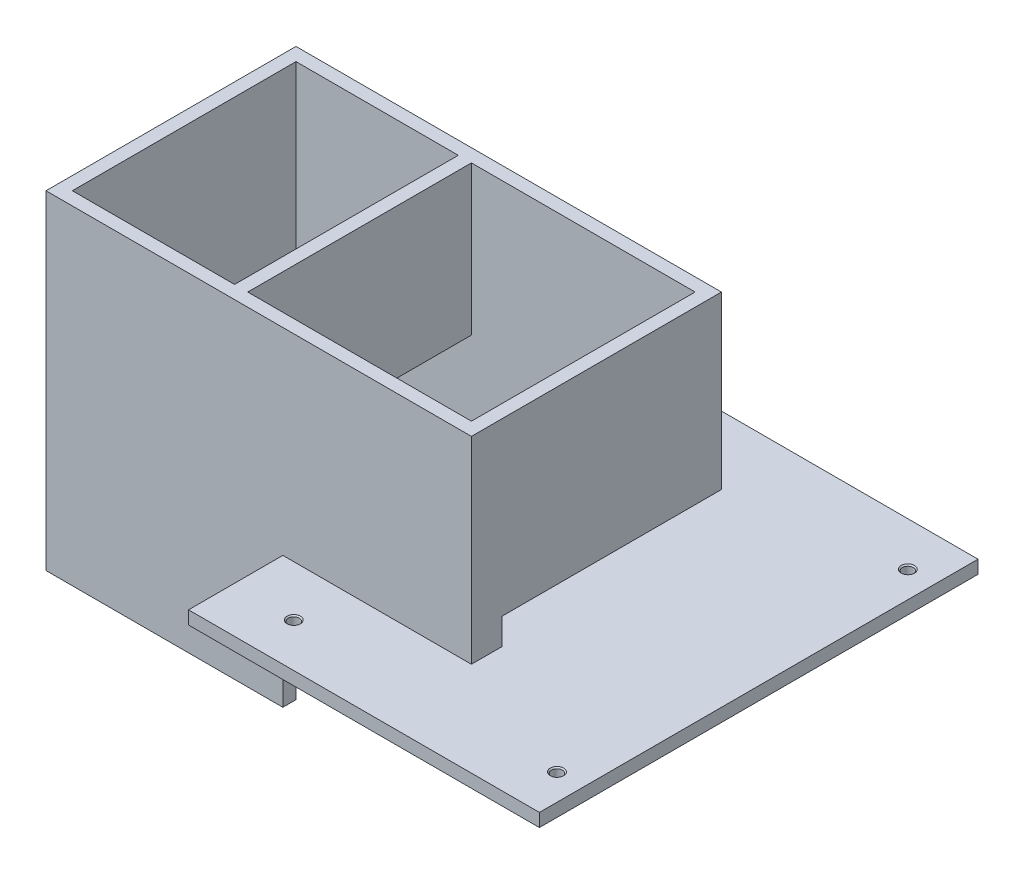
SolidWorks part; units mm, degrees
ref_plane "前视基准面" through (0, 0, 0) normal (0, 0, 1) x (1, 0, 0)
ref_plane "上视基准面" through (0, 0, 0) normal (0, 1, 0) x (1, 0, 0)
ref_plane "右视基准面" through (0, 0, 0) normal (1, 0, 0) x (0, 0, -1)
sketch "草图1" plane through (0, 0, 0) normal (0, 1, 0) x (1, 0, 0)
  line L1 (-60.7657, 28.3376) -> (19.2343, 28.3376)
  line L2 (-60.7657, 28.3376) -> (-60.7657, -71.6624)
  line L3 (-60.7657, -71.6624) -> (19.2343, -71.6624)
  line L4 (19.2343, 28.3376) -> (19.2343, -71.6624)
  dimension "D1" = 100
  dimension "D2" = 80
extrude "凸台-拉伸1" add sketch "草图1" along normal blind 3 contours L2 L3 L4 L1
sketch "草图2" plane through (0, 3, 0) normal (0, 1, 0) x (1, 0, 0)
  line L0 (-60.7657, -21.6624) -> (19.2343, -21.6624) construction
  line L1 (-111.7657, 3.8376) -> (-20.7657, 3.8376)
  line L2 (-111.7657, 3.8376) -> (-111.7657, -47.1624)
  line L3 (-111.7657, -47.1624) -> (-20.7657, -47.1624)
  line L4 (-20.7657, 3.8376) -> (-20.7657, -47.1624)
  line L5 (-60.7657, 28.3376) -> (-60.7657, -71.6624) construction
  line L6 (19.2343, 28.3376) -> (19.2343, -71.6624) construction
  line L7 (-114.7657, 6.8376) -> (-114.7657, -50.1624)
  line L8 (-114.7657, -50.1624) -> (-17.7657, -50.1624)
  line L9 (-17.7657, 6.8376) -> (-17.7657, -50.1624)
  line L10 (-114.7657, 6.8376) -> (-17.7657, 6.8376)
  dimension "D1" = 51
  dimension "D2" = 40
  dimension "D3" = 51
  dimension "D4" = 3
extrude "凸台-拉伸2" add sketch "草图2" along normal blind 45
sketch "草图3" plane through (0, 0, -3.8376) normal (0, 0, 1) x (1, 0, 0)
  line L0 (-74.7657, 48) -> (-74.7657, 14)
  line L1 (-114.7657, 48) -> (-17.7657, 48) construction
  line L3 (-74.7657, 14) -> (-71.7657, 14)
  line L4 (-71.7657, 14) -> (-71.7657, 48)
  line L5 (-71.7657, 48) -> (-74.7657, 48)
  line L6 (-17.7657, 48) -> (-17.7657, 3) construction
  line L7 (-114.7657, 3) -> (-60.7657, 3) construction
  dimension "D1" = 54
  dimension "D2" = 3
  dimension "D3" = 11
extrude "凸台-拉伸3" add sketch "草图3" along normal blind 51
sketch "草图4" plane through (0, 0, -6.8376) normal (0, 0, -1) x (-1, 0, 0)
  line L0 (17.7657, 3) -> (47.7657, 3)
  line L1 (17.7657, 3) -> (60.7657, 3) construction
  line L2 (47.7657, 3) -> (47.7657, 9)
  line L3 (47.7657, 9) -> (17.7657, 9)
  line L4 (17.7657, 48) -> (17.7657, 3) construction
  line L5 (17.7657, 9) -> (17.7657, 3)
  dimension "D1" = 30
  dimension "D2" = 6
extrude "切除-拉伸2" cut sketch "草图4" against normal blind 50
sketch "草图5" plane through (0, 3, 0) normal (0, -1, 0) x (1, 0, 0)
  line L0 (-111.7657, 47.1624) -> (-111.7657, -3.8376)
  line L1 (-111.7657, -3.8376) -> (-60.7657, -3.8376)
  line L2 (-60.7657, -3.8376) -> (-60.7657, 47.1624)
  line L3 (-60.7657, 47.1624) -> (-111.7657, 47.1624)
  line L4 (-114.7657, 50.1624) -> (-114.7657, -6.8376)
  line L5 (-114.7657, -6.8376) -> (-57.7657, -6.8376)
  line L6 (-57.7657, -6.8376) -> (-57.7657, 50.1624)
  line L7 (-57.7657, 50.1624) -> (-114.7657, 50.1624)
  dimension "D1" = 3
extrude "凸台-拉伸4" add sketch "草图5" along normal blind 30
sketch "草图6" plane through (0, 3, 0) normal (0, 1, 0) x (1, 0, 0)
  line L0 (-60.7657, -21.6624) -> (19.2343, -21.6624) construction
  line L1 (-60.7657, 3.8376) -> (-60.7657, -47.1624) construction
  line L2 (19.2343, 28.3376) -> (19.2343, -71.6624) construction
  line L3 (-60.7657, 28.3376) -> (-60.7657, 6.8376) construction
  line L4 (-60.7657, 28.3376) -> (19.2343, 28.3376) construction
  point P0 (-46.7657, 18.3376)
  point P1 (-46.7657, -61.6624)
  point P8 (13.2343, -61.6624)
  point P13 (13.2343, 18.3376)
  dimension "D1" = 14
  dimension "D2" = 10
  dimension "D3" = 10
  dimension "D4" = 60
hole_wizard "M3 螺纹孔1" positions "草图7" profile "草图8" tap size "M3" standard "GB" end condition through all
sketch "草图7" plane through (0, 3, 0) normal (0, 1, 0) x (1, 0, 0)
  point P0 (-46.7657, 18.3376)
  point P3 (13.2343, 18.3376)
  point P6 (13.2343, -61.6624)
  point P9 (-46.7657, -61.6624)
sketch "草图8" plane through (-46.7657, 3, -18.3376) normal (1, 0, 0) x (0, 0, 1)
  line L0 (0, 0) -> (0, 30)
  line L1 (0, 30) -> (1.25, 30)
  line L2 (1.25, 30) -> (1.25, 0.275)
  line L3 (1.25, 0.275) -> (1.525, 0)
  line L5 (1.525, 0) -> (0, 0)
  line L6 (-1.25, 0.275) -> (-1.525, 0) construction
  line L11 (0, -6.35) -> (0, 107.95) construction
  dimension "通孔螺纹孔钻头直径" = 2.5
  dimension "通孔螺纹孔钻头深度" = 30
  dimension "近端锥形沉头孔直径" = 3.05
  dimension "近端锥形沉头孔角度" = 90
cosmetic thread "孔螺蚊线1" parameters "D2"=3
cosmetic thread "孔螺蚊线2" parameters "D2"=3
cosmetic thread "孔螺蚊线3" parameters "D2"=3
cosmetic thread "孔螺蚊线4" parameters "D2"=3
sketch "草图9" plane through (0, -27, 0) normal (0, -1, 0) x (-1, 0, 0)
  line L0 (57.7657, -50.1624) -> (114.7657, -50.1624) construction
  line L1 (60.7657, -50.1624) -> (57.7657, -50.1624)
  line L2 (60.7657, -50.1624) -> (60.7657, 6.8376)
  line L3 (60.7657, 6.8376) -> (57.7657, 6.8376)
  line L4 (57.7657, -50.1624) -> (57.7657, 6.8376)
  line L5 (57.7657, 6.8376) -> (60.7657, 6.8376) construction
  line L6 (114.7657, 6.8376) -> (57.7657, 6.8376) construction
  dimension "D1" = 3
extrude "切除-拉伸3" cut sketch "草图9" against normal blind 27
